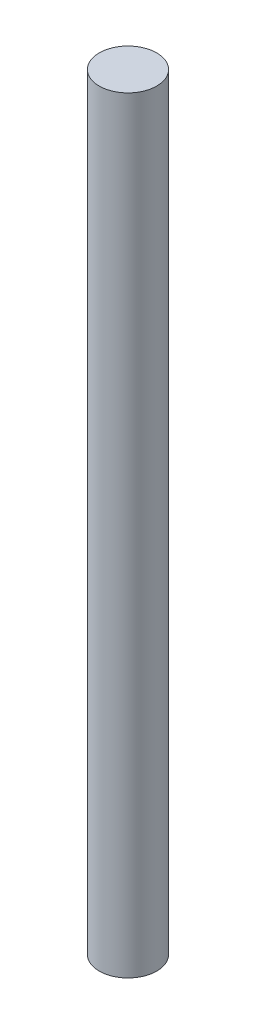
SolidWorks part; units mm, degrees
ref_plane "Front Plane" through (0, 0, 0) normal (0, 0, 1) x (1, 0, 0)
ref_plane "Top Plane" through (0, 0, 0) normal (0, 1, 0) x (1, 0, 0)
ref_plane "Right Plane" through (0, 0, 0) normal (1, 0, 0) x (0, 0, -1)
sketch "Sketch1" plane through (0, 0, 0) normal (0, 1, 0) x (1, 0, 0)
  circle A0 centre (0, 0) radius 7.5
  dimension "D1" = 15
extrude "Boss-Extrude1" add sketch "Sketch1" along normal mid plane 200
